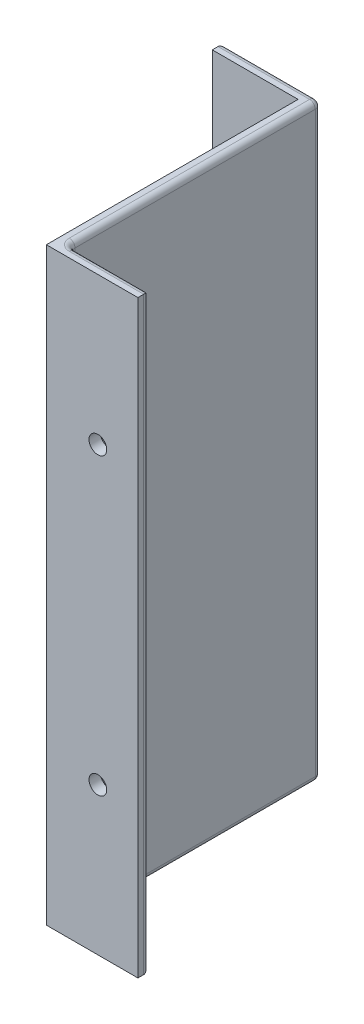
SolidWorks part; units mm, degrees
ref_plane "Plano frontal" through (0, 0, 0) normal (0, 0, 1) x (1, 0, 0)
ref_plane "Plano superior" through (0, 0, 0) normal (0, 1, 0) x (1, 0, 0)
ref_plane "Plano direito" through (0, 0, 0) normal (1, 0, 0) x (0, 0, -1)
sketch "Esboço1" plane through (0, 0, 0) normal (0, 1, 0) x (1, 0, 0)
  line L0 (0, 0) -> (16, 0)
  line L1 (16, 0) -> (16, 2)
  line L2 (16, 2) -> (2, 2)
  line L3 (2, 2) -> (2, 46)
  line L4 (2, 46) -> (-15, 46)
  line L5 (-15, 46) -> (-15, 44)
  line L6 (-15, 44) -> (0, 44)
  line L7 (0, 44) -> (0, 0)
  dimension "D1" = 16
  dimension "D2" = 2
  dimension "D3" = 2
  dimension "D4" = 2
  dimension "D5" = 44
  dimension "D6" = 17
extrude "Ressalto-extrusão1" add sketch "Esboço1" along normal blind 103
sketch "Esboço2" plane through (0, 0, -2) normal (0, 0, -1) x (-1, 0, 0)
  line L0 (-16, 0) -> (-2, 0) construction
  line L1 (-16, 103) -> (-2, 103) construction
  line L2 (-16, 0) -> (-2, 0) construction
  line L3 (-16, 103) -> (-2, 103) construction
  line L4 (-9, 103) -> (-9, 51.5) construction
  line L5 (-9, 51.5) -> (-16, 51.5) construction
  line L6 (-16, 103) -> (-16, 0) construction
  circle A0 centre (-9, 77.25) radius 1.55
  circle A1 centre (-9, 25.75) radius 1.55
  dimension "D1" = 3.1
extrude "Corte-extrusão1" cut sketch "Esboço2" against normal blind 2
sketch "Esboço3" plane through (0, 0, -2) normal (0, 0, -1) x (-1, 0, 0)
  line L0 (-9, 77.25) -> (-9, 25.75) construction
  text T0 "FONTE 12V"
extrude "Corte-extrusão2" cut sketch "Esboço3" against normal blind 0.5
fillet "Filete1" radius 1 10 edges at (9, 103, -2) (9, 0, -2) (2, 51.5, -2) (2, 103, -24) (2, 0, -24) (-6.5, 103, -46) (-15, 51.5, -46) (-6.5, 0, -46) (16, 51.5, -2) (2, 51.5, -46)
equation "\"D3@Esboço1\"=\"D2@Esboço1\""
equation "\"D4@Esboço1\"=\"D2@Esboço1\""
